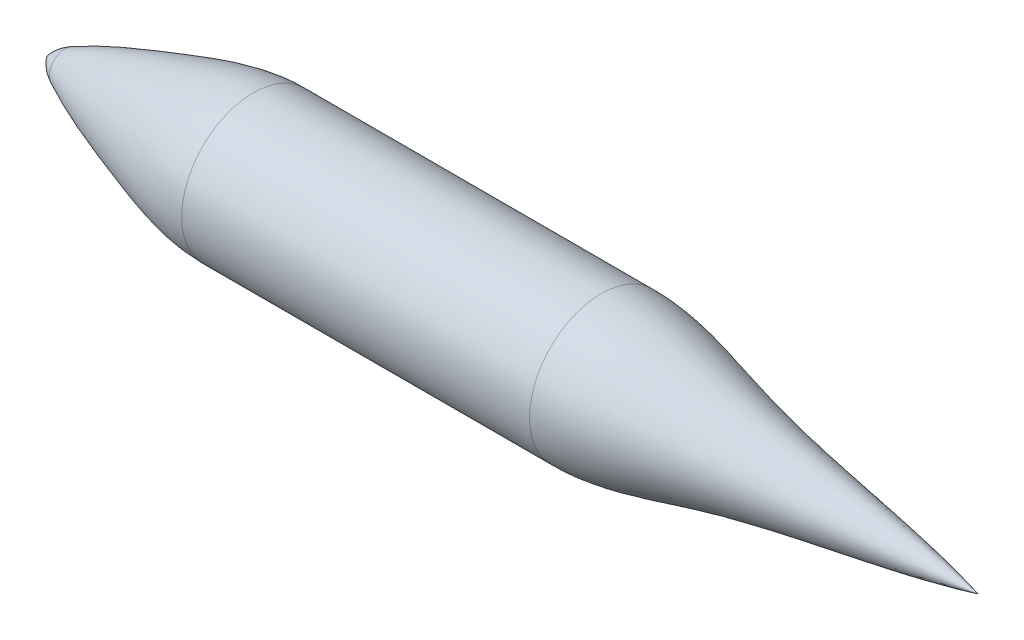
SolidWorks part; units mm, degrees
material "3003-H14"
ref_plane "Piano frontale" through (0, 0, 0) normal (1, 0, 0) x (0, 1, 0)
ref_plane "Piano superiore" through (0, 0, 0) normal (0, 0, 1) x (0, 1, 0)
ref_plane "Piano destro" through (0, 0, 0) normal (0, 1, 0) x (-1, 0, 0)
sketch "Schizzo6" plane through (0, 0, 0) normal (0, 1, 0) x (-1, 0, 0)
  line L0 (312.8, 33.1) -> (173.8, 33.1)
  line L1 (0, 0) -> (407.9842, 0)
  line L2 (407.9842, 0) -> (429.4842, 0)
  line L3 (312.8, 33.1) -> (334.3, 33.1)
  spline S0 degree 3 poles (334.3, 33.1) (349.7122, 33.1) (379.2197, 23.4523) (407.7417, 14.0122) (421.2, 7.24) knots 0 0 0 0 0.507345 1 1 1 1
  spline S1 degree 3 poles (421.2, 7.24) (424.5854, 5.5365) (427.3468, 3.1232) (429.4842, 0) knots 0 0 0 0 1 1 1 1
  spline S2 degree 3 poles (0, 0) (25.1897, 6.4207) (65.5245, 11.9059) (123.6018, 23.1982) (154.2741, 33.1) (173.8, 33.1) knots 0 0 0 0 0.440523 0.69482 1 1 1 1
  point P0 (0, 0)
  point P1 (312.8, 33.1)
  point P3 (173.8, 33.1)
  point P4 (399.7, 7.24)
  point P7 (203.9921, 0)
  point P13 (0, 0)
  point P15 (0, 0)
  dimension "D1" = 173.8
  dimension "D2" = 399.7
  dimension "D3" = 312.8
  dimension "D4" = 33.1
  dimension "D5" = 7.24
revolve "Rivoluzione1" add sketch "Schizzo6" angle 360 about L1
sketch "Schizzo7" plane through (0, 0, 0) normal (0, 0, 1) x (0, 1, 0)
  line L0 (0, 218.9921) -> (0, 507.0487) construction
  line L1 (-40.9226, 218.9921) -> (35.4581, 218.9921) construction
  point P4 (0, 218.9921)
sketch "Schizzo8" plane through (0, 0, 0) normal (0, 1, 0) x (-1, 0, 0)
  line L0 (218.9921, 0) -> (218.9921, -815.3876) construction
equation "\"D\"= 208 / pi"
equation "\"R\"= \"D\" / 2"
equation "\"NoseRatio\"= 3"
equation "\"L_cyl\" = 168"
equation "\"L_nose\"= \"NoseRatio\" * \"D\""
equation "\"L_total\"= \"L_nose\" + \"L_cyl\""
equation "\"TailRatio\"= 1.5"
equation "\"L_tail\"= \"TailRatio\" * \"D\""
equation "\"R_tip\"= 0.03 * \"D\""
